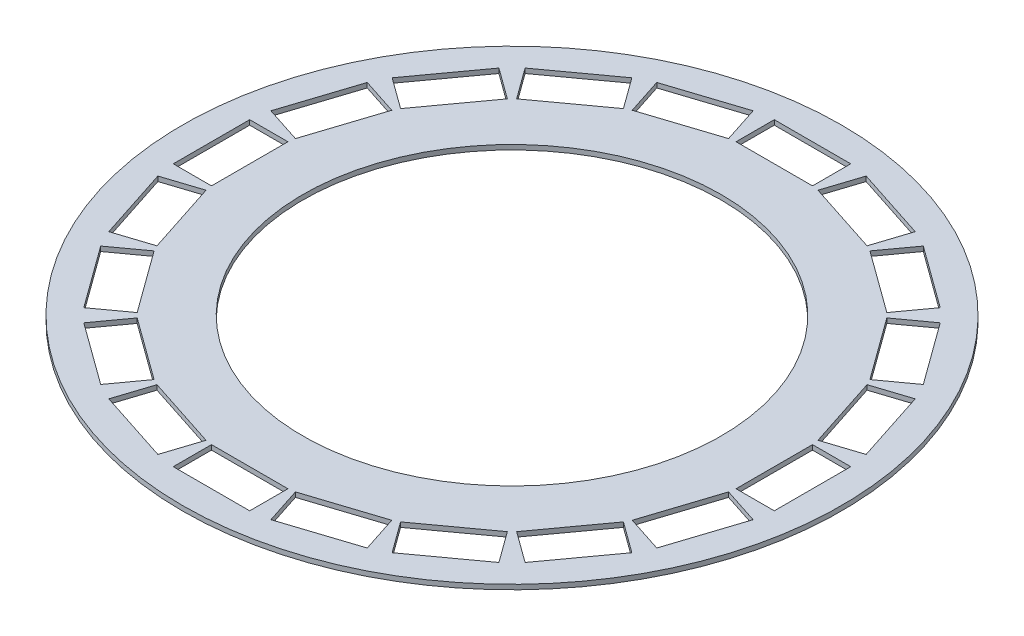
SolidWorks part; units mm, degrees
material "Hexcel AS4C (3000 Filaments)"
ref_plane "Front Plane" through (0, 0, 0) normal (0, 0, 1) x (1, 0, 0)
ref_plane "Top Plane" through (0, 0, 0) normal (0, 1, 0) x (1, 0, 0)
ref_plane "Right Plane" through (0, 0, 0) normal (1, 0, 0) x (0, 0, -1)
sketch "Sketch1" plane through (0, 0, 0) normal (0, 0, 1) x (1, 0, 0)
  line L0 (-69.5, 7.3725) -> (-69.5, 5.785) construction
  line L1 (-69.5, 7.3725) -> (-109.5, 7.3725) construction
  line L2 (-109.5, 5.785) -> (-69.5, 5.785) construction
  line L3 (-109.5, 7.3725) -> (-109.5, 5.785) construction
  line L4 (-69.5, 7.3725) -> (-69.5, 5.785)
  line L5 (-69.5, 7.3725) -> (-109.5, 7.3725)
  line L6 (-109.5, 5.785) -> (-69.5, 5.785)
  line L7 (-109.5, 7.3725) -> (-109.5, 5.785)
  line L8 (0, -200069.0475) -> (0, 200086.9028) construction
  line L9 (0, -200069.0475) -> (0, 200086.9028) construction
revolve "Revolve1" add sketch "Sketch1" angle 360 about L9
sketch "Sketch2" plane through (0, 7.3725, 0) normal (0, 1, 0) x (1, 0, 0)
  line L0 (0, 93.5) -> (0, 0) construction
  line L1 (-12.7, 99.85) -> (12.7, 99.85)
  line L2 (-12.7, 99.85) -> (-12.7, 87.15)
  line L3 (-12.7, 87.15) -> (12.7, 87.15)
  line L4 (12.7, 99.85) -> (12.7, 87.15)
  line L5 (-12.7, 99.85) -> (12.7, 87.15) construction
  line L6 (-12.7, 87.15) -> (12.7, 99.85) construction
  line L7 (0, 100) -> (0, 87) construction
  circle A0 centre (0, 0) radius 87 construction
  circle A1 centre (0, 0) radius 100 construction
  circle A2 centre (0, 0) radius 87 construction
  circle A3 centre (0, 0) radius 100 construction
  point P0 (0, 93.5)
  dimension "D1" = 12.7
  dimension "D2" = 25.4
extrude "Cut-Extrude1" cut sketch "Sketch2" against normal through all
pattern_circular "CirPattern1" count 20 over 360 about axis through (0, 0, 0) along (0, 1, 0) of "Cut-Extrude1"
